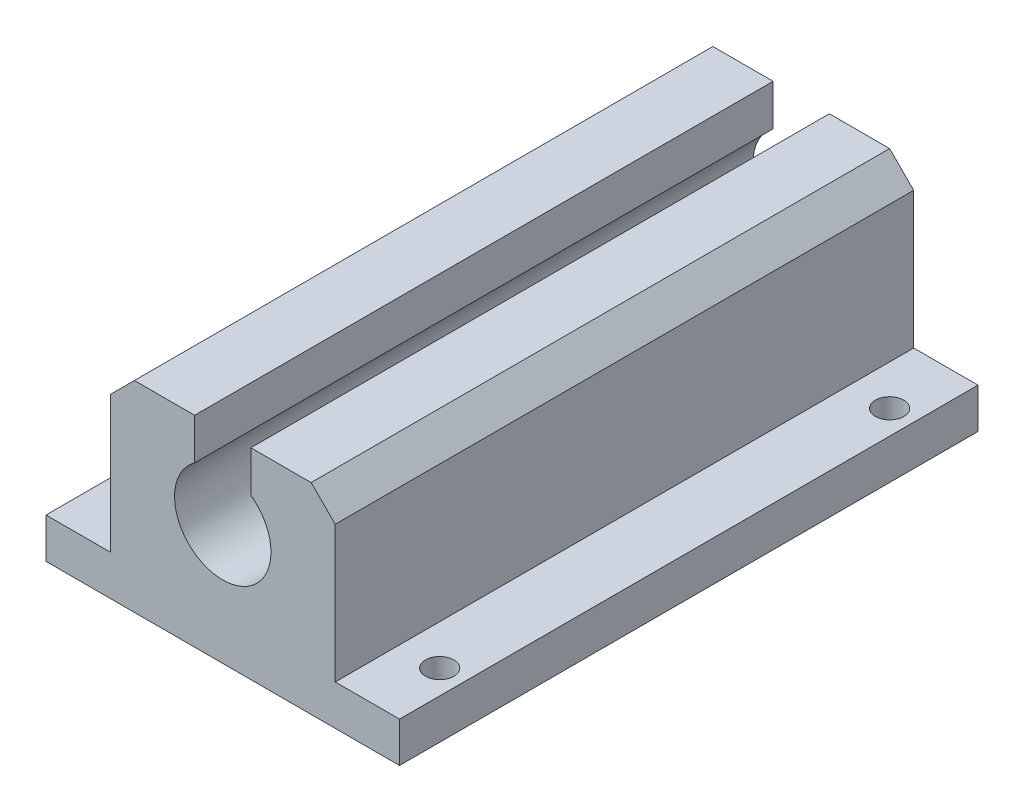
SolidWorks part; units mm, degrees
ref_plane "Front" through (0, 0, 0) normal (0, 0, 1) x (1, 0, 0)
ref_plane "Top" through (0, 0, 0) normal (0, 1, 0) x (1, 0, 0)
ref_plane "Right" through (0, 0, 0) normal (1, 0, 0) x (0, 0, -1)
sketch "Sketch1" plane through (0, 0, 0) normal (0, 0, 1) x (1, 0, 0)
  line L0 (22.225, 15.875) -> (5.5563, 15.875)
  line L1 (5.5563, 15.875) -> (5.5563, 7.7365)
  line L2 (22.225, 15.875) -> (22.225, -15.875)
  line L3 (22.225, -15.875) -> (34.925, -15.875)
  line L4 (34.925, -15.875) -> (34.925, -23.8125)
  line L5 (34.925, -23.8125) -> (-34.925, -23.8125)
  line L6 (-34.925, -23.8125) -> (-34.925, -15.875)
  line L7 (-34.925, -15.875) -> (-22.225, -15.875)
  line L8 (-22.225, -15.875) -> (-22.225, 15.875)
  line L9 (-22.225, 15.875) -> (-5.5562, 15.875)
  line L10 (-5.5562, 15.875) -> (-5.5562, 7.7365)
  arc A0 (-5.5562, 7.7365) -> (5.5563, 7.7365) centre (0, 0) ccw
  dimension "D2" = 9.525
  dimension "D4" = 23.8125
  dimension "D1" = 69.85
  dimension "D3" = 39.6875
  dimension "D5" = 7.9375
  dimension "D6" = 44.45
  dimension "D7" = 11.1125
extrude "Extrude1" add sketch "Sketch1" along normal mid plane 114.3
hole_wizard "#10 Clearance Hole1" positions "Sketch3" profile "Sketch2" hole size "#10" standard "Ansi Inch" end condition up to next
sketch "Sketch3" plane through (0, -23.8125, 0) normal (0, -1, 0) x (1, 0, 0)
  point P0 (-30.1625, -44.45)
  point P1 (30.1625, -44.45)
  point P5 (-30.1625, 44.45)
  point P7 (30.1625, 44.45)
  dimension "D1" = 60.325
  dimension "D2" = 30.1625
  dimension "D3" = 44.45
  dimension "D4" = 88.9
sketch "Sketch2" plane through (-30.1625, -23.8125, -44.45) normal (1, 0, 0) x (0, 0, -1)
  line L0 (0, 0) -> (0, 7.9375)
  line L1 (0, 7.9375) -> (2.8067, 7.9375)
  line L2 (2.8067, 7.9375) -> (2.8067, 0)
  line L5 (2.8067, 0) -> (0, 0)
  line L11 (0, -6.35) -> (0, 107.95) construction
  dimension "Thru Hole Dia." = 5.6134
  dimension "Thru Hole Depth" = 7.9375
chamfer "Chamfer1" distance 4.7625 angle 45 2 edges at (-22.225, 15.875, 0) (22.225, 15.875, 0)
